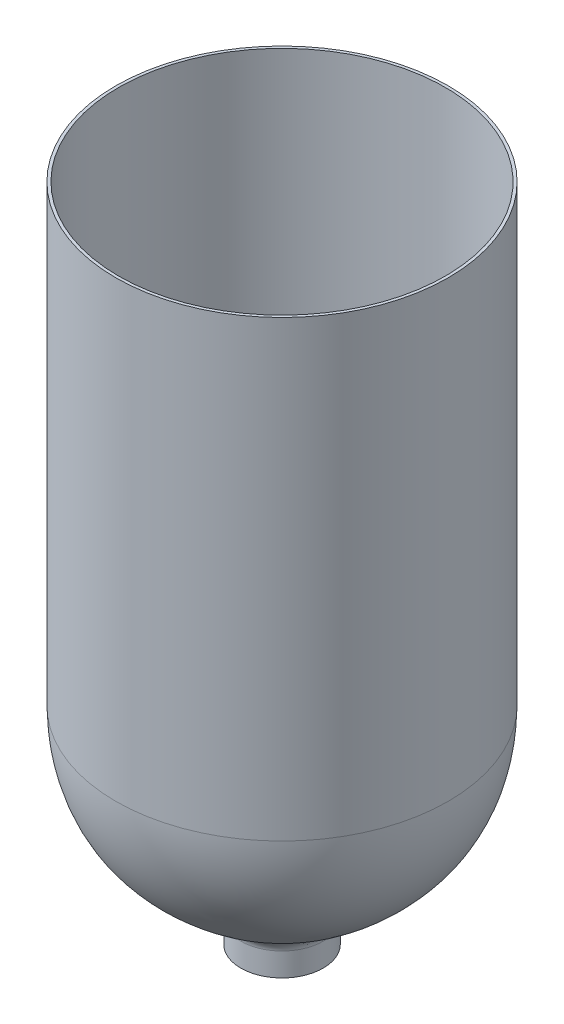
SolidWorks part; units mm, degrees
ref_plane "Front Plane" through (0, 0, 0) normal (0, 0, 1) x (1, 0, 0)
ref_plane "Top Plane" through (0, 0, 0) normal (0, 1, 0) x (1, 0, 0)
ref_plane "Right Plane" through (0, 0, 0) normal (1, 0, 0) x (0, 0, -1)
sketch "Sketch1" plane through (0, 0, 0) normal (0, 0, 1) x (1, 0, 0)
  line L0 (0, 76.8793) -> (0, -96.1386) construction
  line L1 (-55.88, 118.4594) -> (-55.88, -33.9406)
  line L2 (-54.9229, 118.4594) -> (-54.9229, -33.4827)
  line L3 (-55.88, 118.4594) -> (-54.9229, 118.4594)
  line L4 (-13.8515, -95.6807) -> (-13.8515, -103.5211)
  line L5 (-12.8897, -95.6807) -> (-12.8897, -103.5211)
  line L6 (-13.8515, -103.5211) -> (-12.8897, -103.5211)
  spline S0 degree 3 poles (-55.88, -33.9406) (-54.9906, -80.0809) (-14.574, -85.8977) (-13.8515, -95.6807) knots 0 0 0 0 0.984738 0.984738 0.984738 0.984738
  spline S1 degree 3 poles (-54.9229, -33.4827) (-54.0197, -80.3381) (-12.3546, -85.6104) (-12.8897, -95.6807) knots 0 0 0 0 1 1 1 1
  dimension "D1" = 55.88
  dimension "D2" = 152.4
revolve "Revolve2" add sketch "Sketch1" angle 360 about L0
